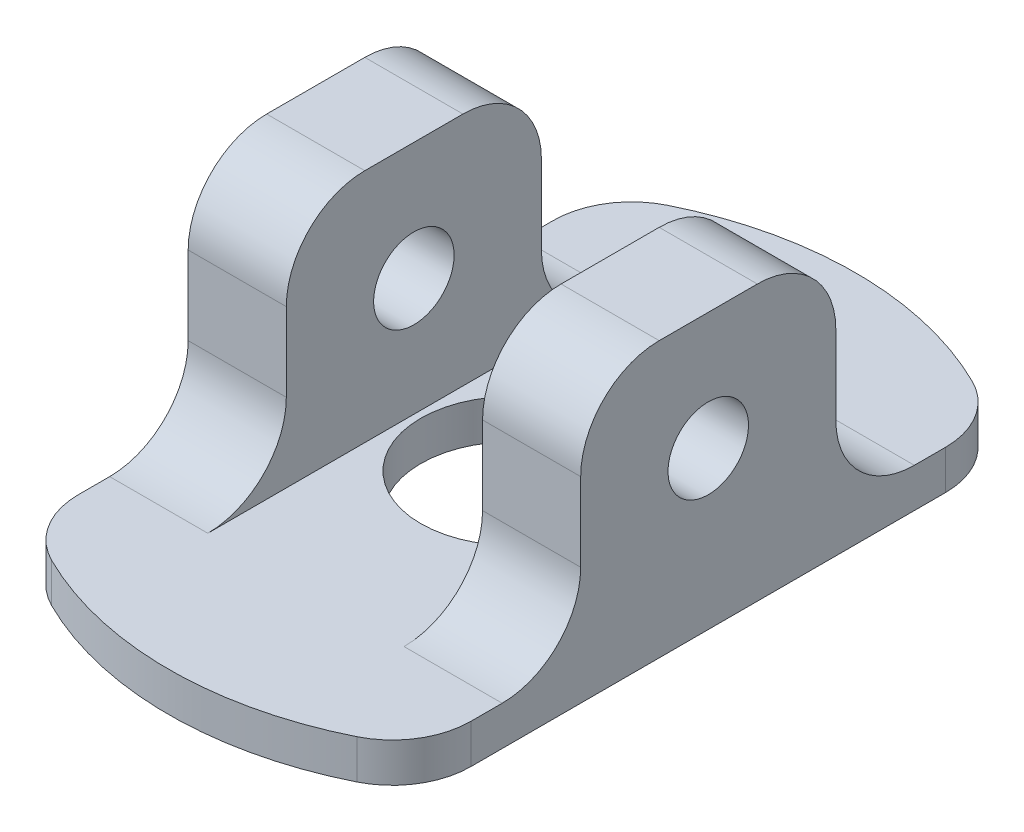
SolidWorks part; units mm, degrees
ref_plane "Front Plane" through (0, 0, 0) normal (0, 0, 1) x (1, 0, 0)
ref_plane "Top Plane" through (0, 0, 0) normal (0, 1, 0) x (1, 0, 0)
ref_plane "Right Plane" through (0, 0, 0) normal (1, 0, 0) x (0, 0, -1)
sketch "Sketch1" plane through (0, 0, 0) normal (0, 1, 0) x (1, 0, 0)
  circle A0 centre (0, 0) radius 4.65
  dimension "D1" = 9.3
extrude "Boss-Extrude1" add sketch "Sketch1" along normal blind 12
sketch "Sketch2" plane through (0, 12, 0) normal (0, 1, 0) x (1, 0, 0)
  circle A0 centre (0, 0) radius 17.5
  dimension "D1" = 35
extrude "Boss-Extrude2" add sketch "Sketch2" along normal blind 2
sketch "Sketch3" plane through (0, 14, 0) normal (0, 1, 0) x (1, 0, 0)
  line L0 (0, 0) -> (0, 17.5) construction
  line L2 (5, 6.5) -> (10, 6.5)
  line L3 (5, 6.5) -> (5, -6.5)
  line L4 (5, -6.5) -> (10, -6.5)
  line L5 (10, 6.5) -> (10, -6.5)
  circle A0 centre (0, 0) radius 17.5 construction
  point P9 (5, 0)
  dimension "D1" = 5
  dimension "D2" = 13
  dimension "D3" = 5
extrude "Boss-Extrude3" add sketch "Sketch3" along normal blind 12 contours L2 L5 L4 L3
mirror "Mirror1" about plane through (0, 0, 0) normal (1, 0, 0) of "Boss-Extrude3"
fillet "Fillet1" radius 4 4 edges at (-7.5, 26, -6.5) (7.5, 26, -6.5) (7.5, 26, 6.5) (-7.5, 26, 6.5)
fillet "Fillet2" radius 4 4 edges at (7.5, 14, -6.5) (-7.5, 14, -6.5) (-7.5, 14, 6.5) (7.5, 14, 6.5)
sketch "Sketch4" plane through (0, 14, 0) normal (0, 1, 0) x (1, 0, 0)
  line L0 (10, 0) -> (10, 14.3614)
  line L1 (10, 2.5) -> (10, -2.5) construction
  line L2 (10, 14.3614) -> (24.3824, 14.3614)
  line L3 (24.3824, 14.3614) -> (24.3824, -16.5205)
  line L4 (24.3824, -16.5205) -> (10, -16.5205)
  line L5 (10, -16.5205) -> (10, 0)
  circle A1 centre (0, 0) radius 17.5
  circle A2 centre (0, 0) radius 17.5
  circle M6 centre (0, 0) radius 17.5
  line M8 (10, 10.5) -> (10, -10.5)
  dimension "D1" = 0
extrude "Cut-Extrude1" cut sketch "Sketch4" against normal through all contours L5 L0 M6 M8
mirror "Mirror2" about plane through (0, 0, 0) normal (1, 0, 0) of "Cut-Extrude1"
sketch "Sketch5" plane through (10, 0, 0) normal (1, 0, 0) x (0, 0, -1)
  line L0 (-6.5, 22) -> (-6.5, 18) construction
  line L1 (2.5, 26) -> (-2.5, 26) construction
  circle A0 centre (0, 20) radius 2.05
  point P4 (-6.5, 20)
  point P7 (0, 26)
  dimension "D1" = 4.1
extrude "Cut-Extrude2" cut sketch "Sketch5" against normal blind 70
fillet "Fillet3" radius 4 4 edges at (10, 13, 14.3614) (10, 13, -14.3614) (-10, 13, -14.3614) (-10, 13, 14.3614)
sketch "Sketch6" plane through (0, 0, 0) normal (0, -1, 0) x (1, 0, 0)
  circle A1 centre (0, 0) radius 4.65
  circle A2 centre (0, 0) radius 4.65
  dimension "D1" = 0
extrude "Cut-Extrude3" cut sketch "Sketch6" against normal through all
